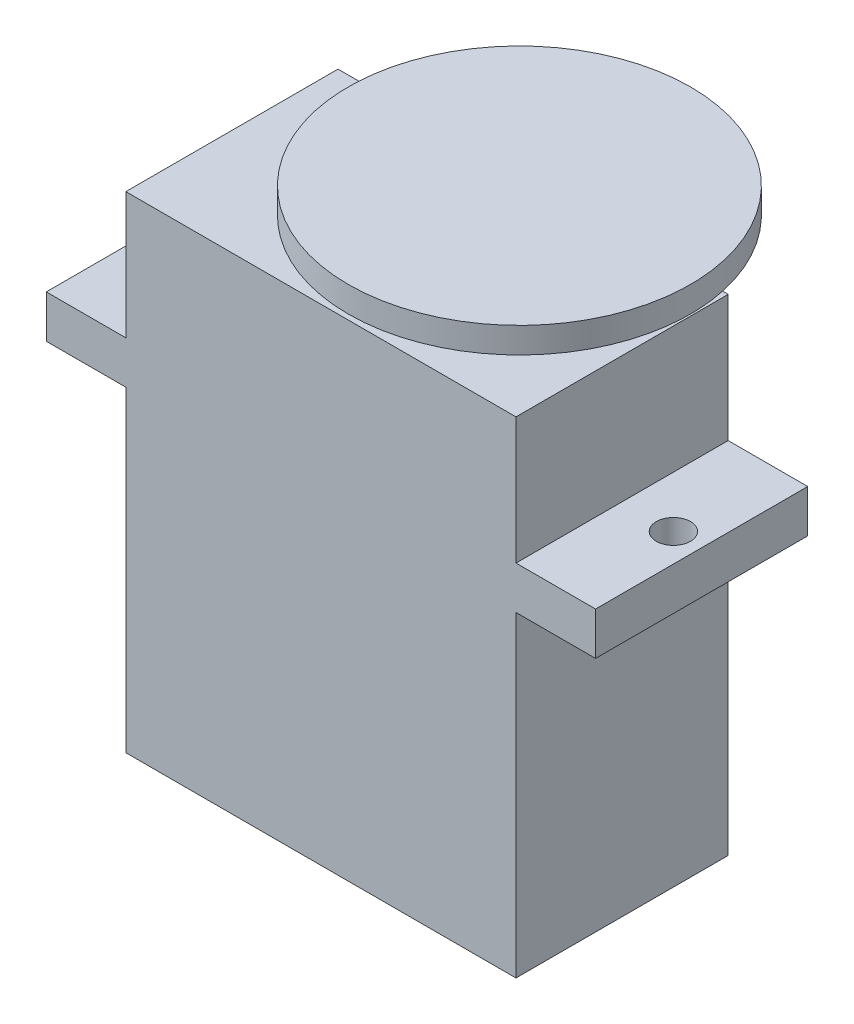
SolidWorks part; units mm, degrees
ref_plane "Front Plane" through (0, 0, 0) normal (0, 0, 1) x (1, 0, 0)
ref_plane "Top Plane" through (0, 0, 0) normal (0, 1, 0) x (1, 0, 0)
ref_plane "Right Plane" through (0, 0, 0) normal (1, 0, 0) x (0, 0, -1)
other "Center of Mass"
sketch "Sketch2" plane through (0, 0, 0) normal (0, 1, 0) x (1, 0, 0)
  line L1 (-16.05, -6.2) -> (16.05, -6.2)
  line L2 (-16.05, -6.2) -> (-16.05, 6.2)
  line L3 (-16.05, 6.2) -> (16.05, 6.2)
  line L4 (16.05, -6.2) -> (16.05, 6.2)
  line L5 (-16.05, -6.2) -> (16.05, 6.2) construction
  line L6 (-16.05, 6.2) -> (16.05, -6.2) construction
  point P0 (0, 0)
  dimension "D1" = 12.4
  dimension "D2" = 32.1
extrude "Boss-Extrude1" add sketch "Sketch2" along normal blind 2.5
sketch "Sketch3" plane through (0, 0, 0) normal (0, -1, 0) x (-1, 0, 0)
  line L0 (16.05, -6.2) -> (-16.05, -6.2) construction
  line L1 (11.4, 6.2) -> (-11.4, 6.2)
  line L2 (11.4, 6.2) -> (11.4, -6.2)
  line L3 (11.4, -6.2) -> (-11.4, -6.2)
  line L4 (-11.4, 6.2) -> (-11.4, -6.2)
  line L5 (11.4, 6.2) -> (-11.4, -6.2) construction
  line L6 (11.4, -6.2) -> (-11.4, 6.2) construction
  point P0 (0, 0)
  dimension "D1" = 22.8
  dimension "D2" = 12.4
extrude "Boss-Extrude2" add sketch "Sketch3" along normal blind 18.5
sketch "Sketch4" plane through (0, 2.5, 0) normal (0, 1, 0) x (1, 0, 0)
  line L0 (16.05, 6.2) -> (-16.05, 6.2) construction
  line L1 (-11.4, -6.2) -> (11.4, -6.2)
  line L2 (-11.4, -6.2) -> (-11.4, 6.2)
  line L3 (-11.4, 6.2) -> (11.4, 6.2)
  line L4 (11.4, -6.2) -> (11.4, 6.2)
  line L5 (-11.4, -6.2) -> (11.4, 6.2) construction
  line L6 (-11.4, 6.2) -> (11.4, -6.2) construction
  point P0 (0, 0)
  dimension "D1" = 22.8
extrude "Boss-Extrude3" add sketch "Sketch4" along normal blind 7.4
sketch "Sketch5" plane through (0, 9.9, 0) normal (0, 1, 0) x (1, 0, 0)
  line L0 (-11.4, 0) -> (13.7542, 0) construction
  line L1 (-11.4, 6.2) -> (-11.4, -6.2) construction
  line L2 (11.4, -6.2) -> (11.4, 6.2) construction
  circle A0 centre (5.4, 0) radius 2.5
  dimension "D1" = 5
  dimension "D2" = 6
extrude "Boss-Extrude4" add sketch "Sketch5" along normal blind 4.1
sketch "Sketch6" plane through (0, 2.5, 0) normal (0, 1, 0) x (1, 0, 0)
  line L0 (-16.05, 0) -> (17.066, 0) construction
  line L1 (-16.05, 6.2) -> (-16.05, -6.2) construction
  line L2 (-11.4, 6.2) -> (-11.4, -6.2) construction
  line L3 (0, 6.2) -> (0, -6.2) construction
  line L4 (11.4, 6.2) -> (-11.4, 6.2) construction
  line L5 (-11.4, -6.2) -> (11.4, -6.2) construction
  circle A0 centre (-14.4, 0) radius 1
  circle A1 centre (14.4, 0) radius 1
  dimension "D1" = 2
  dimension "D2" = 3
extrude "Cut-Extrude1" cut sketch "Sketch6" against normal through all
sketch "Sketch7" plane through (0, 14, 0) normal (0, 1, 0) x (1, 0, 0)
  circle A0 centre (5.4, 0) radius 10
  dimension "D1" = 20
extrude "Boss-Extrude5" add sketch "Sketch7" along normal blind 1.5
